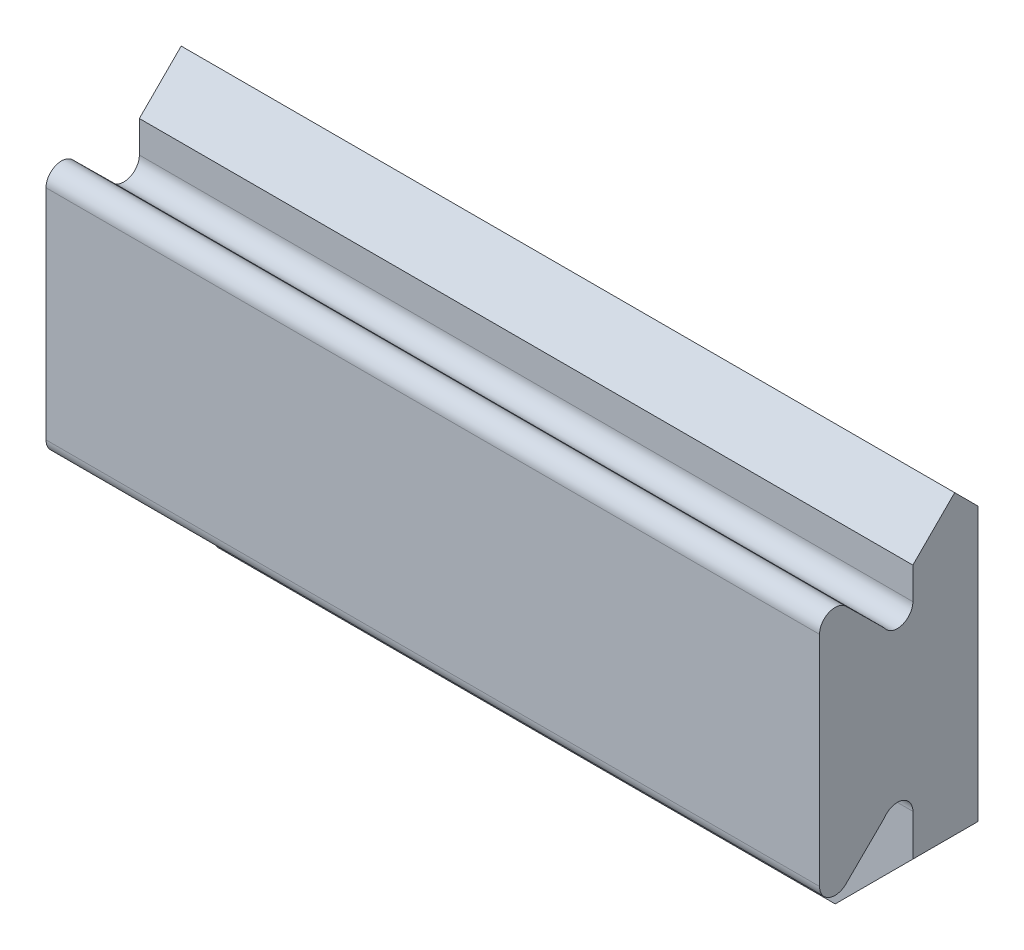
SolidWorks part; units mm, degrees
ref_plane "前视基准面" through (0, 0, 0) normal (0, 0, 1) x (1, 0, 0)
ref_plane "上视基准面" through (0, 0, 0) normal (0, 1, 0) x (1, 0, 0)
ref_plane "右视基准面" through (0, 0, 0) normal (1, 0, 0) x (0, 0, -1)
other "Configuration Table"
sketch "草图1" plane through (0, 0, 0) normal (1, 0, 0) x (0, 0, -1)
  line L0 (-9.8418, 9.874) -> (-12.6045, 12.6044)
  line L1 (-14.3116, 11.8973) -> (-14.3116, -2.1592)
  line L2 (-8.3012, 10.7153) -> (-8.3012, 12.754)
  line L3 (-8.3012, 12.754) -> (-5.6082, 15.447)
  line L4 (-14.3116, 4.8691) -> (-3.3012, 4.8691) construction
  line L5 (-8.3012, -0.9771) -> (-8.3012, -3.0159)
  line L6 (-9.8418, -0.1359) -> (-12.6045, -2.8663)
  line L7 (-8.3012, -3.0159) -> (-8.3012, -8.6409)
  line L8 (-8.3012, -8.6409) -> (-3.3012, -8.6409)
  line L9 (-3.3012, -8.6409) -> (-3.3012, 13.1399)
  line L10 (-3.3012, 13.1399) -> (-5.6082, 15.447)
  arc A0 (-12.6045, 12.6044) -> (-14.3116, 11.8973) centre (-13.3116, 11.8973) ccw
  arc A1 (-10.136, 10.1647) -> (-8.3012, 10.7153) centre (-9.3012, 10.7153) ccw
  arc A2 (-10.136, -0.4266) -> (-8.3012, -0.9771) centre (-9.3012, -0.9771) cw
  arc A3 (-12.6045, -2.8663) -> (-14.3116, -2.1592) centre (-13.3116, -2.1592) cw
extrude "凸台-拉伸1" add sketch "草图1" along normal blind 49.8 contours L4 L1 A3 L6 A2 L5 L7 L8 L9 | L1 L4 L9 L10 L3 L2 A1 L0 A0
chamfer "倒角1" distance 5 angle 45 2 edges at (0, -8.6409, 5.8012) (49.8, -8.6409, 5.8012)
sketch "草图3" plane through (49.8, 0, 0) normal (1, 0, 0) x (0, 0, -1)
  line L0 (-3.3012, 13.1399) -> (-5.6082, 15.447) construction
  line L1 (-4.1082, 13.947) -> (-3.3012, 13.947)
  line L2 (-4.1082, 13.947) -> (-4.1082, -8.6409)
  line L3 (-4.1082, -8.6409) -> (-3.3012, -8.6409)
  line L4 (-3.3012, 13.947) -> (-3.3012, -8.6409)
  dimension "D1" = 1.5
extrude "切除-拉伸1" cut sketch "草图3" against normal blind 49.8
